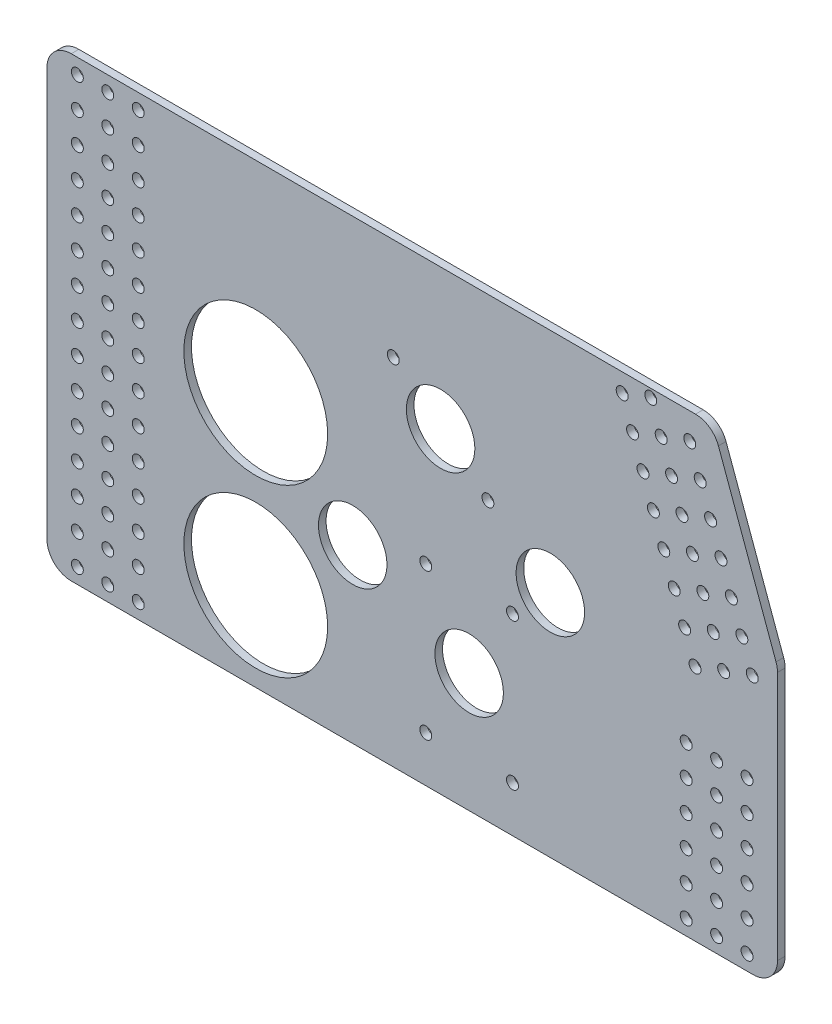
SolidWorks part; units mm, degrees
ref_plane "Front Plane" through (0, 0, 0) normal (0, 0, 1) x (1, 0, 0)
ref_plane "Top Plane" through (0, 0, 0) normal (0, 1, 0) x (1, 0, 0)
ref_plane "Right Plane" through (0, 0, 0) normal (1, 0, 0) x (0, 0, -1)
sketch "Sketch1" plane through (0, 0, 0) normal (0, 0, 1) x (1, 0, 0)
  line B0 (-152.4, 0) -> (152.4, 0)
  line B1 (152.4, 0) -> (152.4, 116.0843)
  line B2 (152.4, 116.0843) -> (125.3149, 190.5)
  line B3 (125.3149, 190.5) -> (-152.4, 190.5)
  line B4 (-152.4, 190.5) -> (-152.4, 0)
  circle B5 centre (-139.7, 184.15) radius 2.4892
  circle B6 centre (-127, 184.15) radius 2.4892
  circle B7 centre (-114.3, 184.15) radius 2.4892
  circle B8 centre (-127, 171.45) radius 2.4892
  circle B9 centre (-114.3, 171.45) radius 2.4892
  circle B10 centre (-127, 158.75) radius 2.4892
  circle B11 centre (-114.3, 158.75) radius 2.4892
  circle B12 centre (-127, 146.05) radius 2.4892
  circle B13 centre (-114.3, 146.05) radius 2.4892
  circle B14 centre (-127, 133.35) radius 2.4892
  circle B15 centre (-114.3, 133.35) radius 2.4892
  circle B16 centre (-127, 120.65) radius 2.4892
  circle B17 centre (-114.3, 120.65) radius 2.4892
  circle B18 centre (-127, 107.95) radius 2.4892
  circle B19 centre (-114.3, 107.95) radius 2.4892
  circle B20 centre (-127, 95.25) radius 2.4892
  circle B21 centre (-114.3, 95.25) radius 2.4892
  circle B22 centre (-127, 82.55) radius 2.4892
  circle B23 centre (-114.3, 82.55) radius 2.4892
  circle B24 centre (-127, 69.85) radius 2.4892
  circle B25 centre (-114.3, 69.85) radius 2.4892
  circle B26 centre (-127, 57.15) radius 2.4892
  circle B27 centre (-114.3, 57.15) radius 2.4892
  circle B28 centre (-127, 44.45) radius 2.4892
  circle B29 centre (-114.3, 44.45) radius 2.4892
  circle B30 centre (-127, 31.75) radius 2.4892
  circle B31 centre (-114.3, 31.75) radius 2.4892
  circle B32 centre (-127, 19.05) radius 2.4892
  circle B33 centre (-114.3, 19.05) radius 2.4892
  circle B34 centre (-127, 6.35) radius 2.4892
  circle B35 centre (-114.3, 6.35) radius 2.4892
  circle B36 centre (-139.7, 171.45) radius 2.4892
  circle B37 centre (-139.7, 158.75) radius 2.4892
  circle B38 centre (-139.7, 146.05) radius 2.4892
  circle B39 centre (-139.7, 133.35) radius 2.4892
  circle B40 centre (-139.7, 120.65) radius 2.4892
  circle B41 centre (-139.7, 107.95) radius 2.4892
  circle B42 centre (-139.7, 95.25) radius 2.4892
  circle B43 centre (-139.7, 82.55) radius 2.4892
  circle B44 centre (-139.7, 69.85) radius 2.4892
  circle B45 centre (-139.7, 57.15) radius 2.4892
  circle B46 centre (-139.7, 44.45) radius 2.4892
  circle B47 centre (-139.7, 31.75) radius 2.4892
  circle B48 centre (-139.7, 19.05) radius 2.4892
  circle B49 centre (-139.7, 6.35) radius 2.4892
  circle B50 centre (87.5907, 182.7494) radius 2.4892
  circle B51 centre (99.5248, 187.093) radius 2.4892
  circle B52 centre (115.8026, 179.5026) radius 2.4892
  circle B53 centre (91.9344, 170.8153) radius 2.4892
  circle B54 centre (103.8685, 175.1589) radius 2.4892
  circle B55 centre (120.1462, 167.5685) radius 2.4892
  circle B56 centre (96.278, 158.8812) radius 2.4892
  circle B57 centre (108.2121, 163.2248) radius 2.4892
  circle B58 centre (124.4899, 155.6344) radius 2.4892
  circle B59 centre (100.6217, 146.9471) radius 2.4892
  circle B60 centre (112.5558, 151.2907) radius 2.4892
  circle B61 centre (128.8335, 143.7003) radius 2.4892
  circle B62 centre (104.9653, 135.013) radius 2.4892
  circle B63 centre (116.8994, 139.3566) radius 2.4892
  circle B64 centre (133.1772, 131.7662) radius 2.4892
  circle B65 centre (109.309, 123.0789) radius 2.4892
  circle B66 centre (121.2431, 127.4226) radius 2.4892
  circle B67 centre (137.5208, 119.8321) radius 2.4892
  circle B68 centre (113.6526, 111.1448) radius 2.4892
  circle B69 centre (125.5867, 115.4885) radius 2.4892
  circle B70 centre (141.8645, 107.898) radius 2.4892
  circle B71 centre (117.9963, 99.2107) radius 2.4892
  circle B72 centre (129.9304, 103.5544) radius 2.4892
  circle B73 centre (146.2081, 95.9639) radius 2.4892
  circle B74 centre (114.3, 69.85) radius 2.4892
  circle B75 centre (127, 69.85) radius 2.4892
  circle B76 centre (139.7, 69.85) radius 2.4892
  circle B77 centre (114.3, 57.15) radius 2.4892
  circle B78 centre (127, 57.15) radius 2.4892
  circle B79 centre (139.7, 57.15) radius 2.4892
  circle B80 centre (114.3, 44.45) radius 2.4892
  circle B81 centre (127, 44.45) radius 2.4892
  circle B82 centre (139.7, 44.45) radius 2.4892
  circle B83 centre (114.3, 31.75) radius 2.4892
  circle B84 centre (127, 31.75) radius 2.4892
  circle B85 centre (139.7, 31.75) radius 2.4892
  circle B86 centre (114.3, 19.05) radius 2.4892
  circle B87 centre (127, 19.05) radius 2.4892
  circle B88 centre (139.7, 19.05) radius 2.4892
  circle B89 centre (114.3, 6.35) radius 2.4892
  circle B90 centre (127, 6.35) radius 2.4892
  circle B91 centre (139.7, 6.35) radius 2.4892
  circle B92 centre (11.8508, 132.0168) radius 14.2875
  circle B93 centre (-24.8197, 71.7449) radius 14.2875
  circle B94 centre (57.6351, 95.7125) radius 14.2875
  circle B95 centre (23.7546, 49.6787) radius 14.2875
  circle B96 centre (-65.2702, 36.9534) radius 29.9974
  circle B97 centre (-65.2702, 106.5494) radius 29.9974
  circle B98 centre (-7.8935, 147.9957) radius 2.4892
  circle B99 centre (31.595, 116.038) radius 2.4892
  circle B100 centre (5.6698, 80.2095) radius 2.4892
  circle B101 centre (41.8394, 80.2095) radius 2.4892
  circle B102 centre (41.8394, 19.1479) radius 2.4892
  circle B103 centre (5.6698, 19.1479) radius 2.4892
sketch_block_instance "Block-OuterPlate-1"
sketch_block "Block-OuterPlate" parameters "D1"=4.9784, "D7"=4.9784, "D8"=4.9784, "D9"=4.9784, "D11"=4.9784, "D12"=4.9784, "D13"=4.9784, "D15"=59.9948, "D16"=59.9948, "D17"=28.575, "D18"=28.575, "D19"=28.575, "D20"=28.575, "D21"=4.9784, "D22"=4.9784, "D23"=4.9784, "D24"=4.9784, "D25"=4.9784, "D26"=4.9784, "D2"=6.35, "D3"=12.7, "D4"=12.7, "D5"=12.7, "D6"=6.35, "D10"=12.7, "D14"=12.7, "D27"=36.1696, "D28"=18.0848, "D29"=30.5308, "D30"=30.5308
extrude "Boss-Extrude1" add sketch "Sketch1" along normal blind 3.175
sketch "Sketch2" plane through (0, 0, 3.175) normal (0, 0, 1) x (1, 0, 0)
  circle A0 centre (146.2081, 95.9639) radius 2.4892
  dimension "D1" = 4.9784
extrude "Boss-Extrude2" add sketch "Sketch2" against normal blind 3.175
fillet "Fillet1" radius 10.16 5 edges at (-152.4, 0, 1.5875) (152.4, 0, 1.5875) (152.4, 116.0843, 1.5875) (125.3149, 190.5, 1.5875) (-152.4, 190.5, 1.5875)
